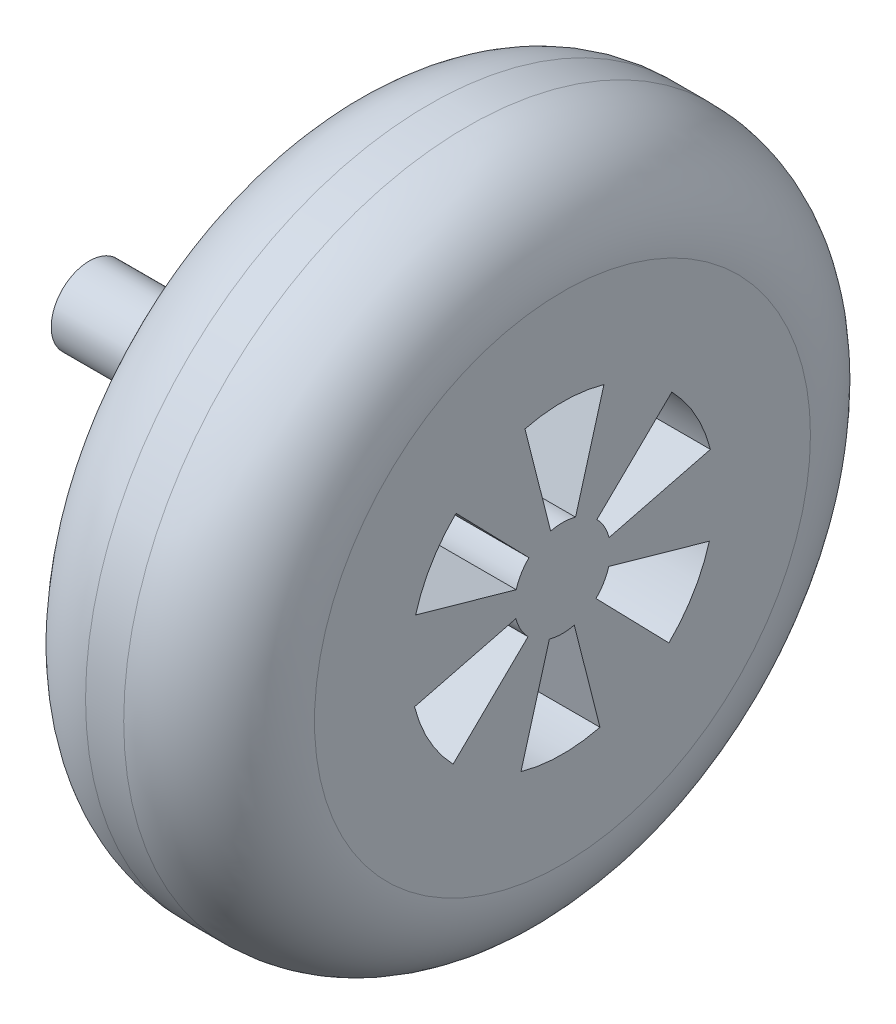
SolidWorks part; units mm, degrees
material "SBR"
ref_plane "Front Plane" through (0, 0, 0) normal (0, 0, 1) x (1, 0, 0)
ref_plane "Top Plane" through (0, 0, 0) normal (0, 1, 0) x (1, 0, 0)
ref_plane "Right Plane" through (0, 0, 0) normal (1, 0, 0) x (0, 0, -1)
sketch "Sketch1" plane through (0, 0, 0) normal (1, 0, 0) x (0, 0, -1)
  circle A0 centre (0, 0) radius 90
  dimension "D1" = 180
extrude "Boss-Extrude1" add sketch "Sketch1" along normal blind 60
fillet "Fillet2" radius 25 2 edges at (60, 0, -90) (0, 0, -90)
sketch "Sketch3" plane through (60, 0, 0) normal (1, 0, 0) x (0, 0, -1)
  line L0 (-2.4575, 9.6933) -> (-9.8299, 38.7734)
  line L1 (2.7184, 9.6234) -> (10.8738, 38.4937)
  line L2 (7.1659, 6.9749) -> (28.6638, 27.8996)
  line L3 (9.6933, 2.4575) -> (38.7734, 9.8299)
  line L4 (9.6234, -2.7184) -> (38.4937, -10.8738)
  line L5 (6.9749, -7.1659) -> (27.8996, -28.6638)
  line L6 (2.4575, -9.6933) -> (9.8299, -38.7734)
  line L7 (-2.7184, -9.6234) -> (-10.8738, -38.4937)
  line L8 (-7.1659, -6.9749) -> (-28.6638, -27.8996)
  line L9 (-9.6933, -2.4575) -> (-38.7734, -9.8299)
  line L10 (-9.6234, 2.7184) -> (-38.4937, 10.8738)
  line L11 (-6.9749, 7.1659) -> (-27.8996, 28.6638)
  circle A0 centre (0, 0) radius 10
  circle A1 centre (0, 0) radius 40
  point P29 (0, 0)
  dimension "D1" = 20
  dimension "D2" = 80
  dimension "D3" = 30
  dimension "D4" = 6
extrude "Cut-Extrude5" cut sketch "Sketch3" against normal through all contours L1 A1 L0 A0 | L3 A1 L2 A0 | L5 A1 L4 A0 | L7 A1 L6 A0 | L9 A1 L8 A0 | L11 A1 L10 A0
sketch "Sketch8" plane through (60, 0, 0) normal (1, 0, 0) x (0, 0, -1)
  circle A0 centre (0, 0) radius 10
extrude "Boss-Extrude2" add sketch "Sketch8" against normal blind 124
sketch "Sketch9" plane through (60, 0, 0) normal (1, 0, 0) x (0, 0, -1)
  circle A0 centre (0, 0) radius 12.5957
extrude "Boss-Extrude3" add sketch "Sketch9" against normal blind 61
